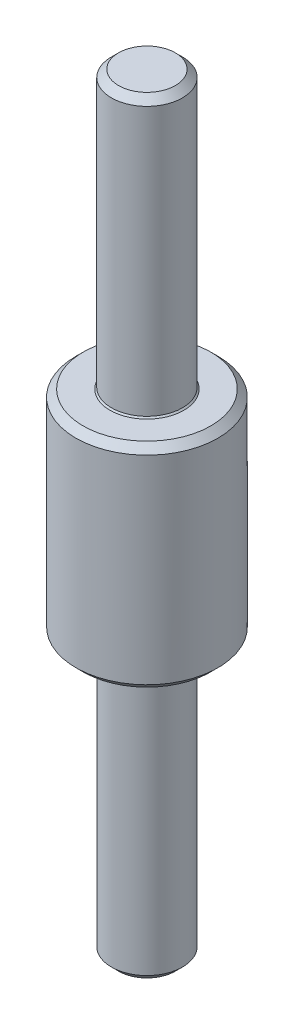
SolidWorks part; units mm, degrees
ref_plane "前视基准面" through (0, 0, 0) normal (0, 0, 1) x (1, 0, 0)
ref_plane "上视基准面" through (0, 0, 0) normal (0, 1, 0) x (1, 0, 0)
ref_plane "右视基准面" through (0, 0, 0) normal (1, 0, 0) x (0, 0, -1)
other "Configuration Table"
sketch "草图1" plane through (0, 0, 0) normal (0, 0, 1) x (1, 0, 0)
  line L0 (0, 17.9143) -> (0, -10.0949) construction
  line L1 (0, 54) -> (5, 54)
  line L2 (5, 54) -> (5, 15)
  line L3 (5, 15) -> (10, 15)
  line L4 (10, 15) -> (10, -15)
  line L5 (10, -15) -> (5, -15)
  line L6 (5, -15) -> (5, -54)
  line L7 (5, -54) -> (0, -54)
  line L8 (0, 0) -> (25.4592, 0) construction
  line L9 (0, 54) -> (0, -54)
  dimension "D1" = 5
  dimension "D2" = 10
  dimension "D3" = 30
  dimension "D4" = 39
  dimension "D5" = 39
revolve "旋转1" add sketch "草图1" angle 360 about L9
chamfer "倒角1" distance 1 angle 45 4 edges at (-10, -15, 0) (-10, 15, 0) (-5, -54, 0) (-5, 54, 0)
chamfer "倒角2" distance 0.2 angle 45 2 edges at (-5, 15, 0) (-5, -15, 0)
